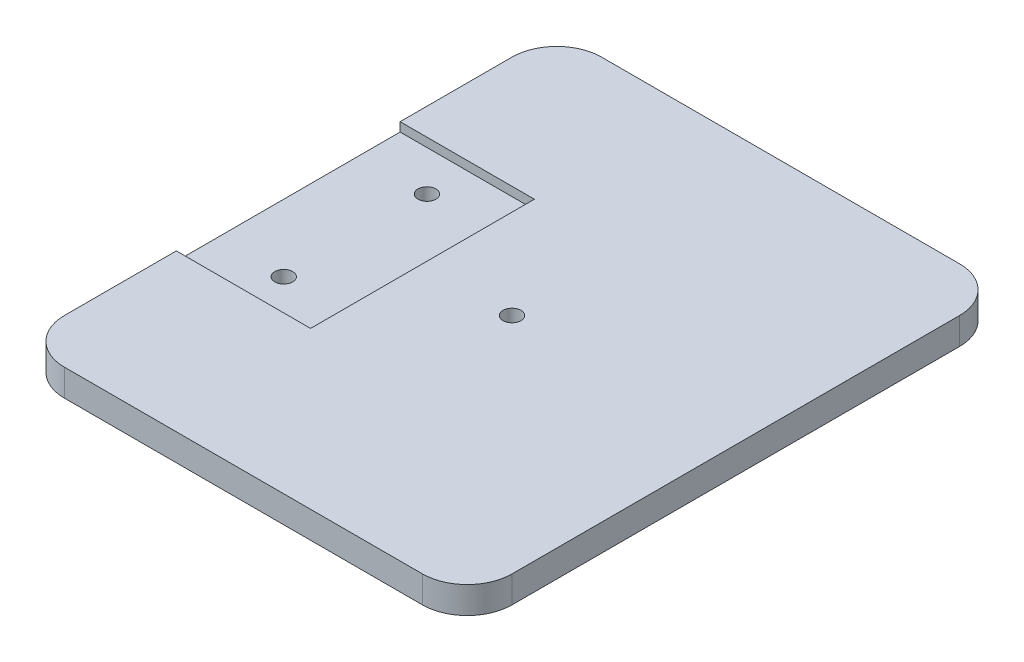
SolidWorks part; units mm, degrees
ref_plane "Front Plane" through (0, 0, 0) normal (0, 0, 1) x (1, 0, 0)
ref_plane "Top Plane" through (0, 0, 0) normal (0, 1, 0) x (1, 0, 0)
ref_plane "Right Plane" through (0, 0, 0) normal (1, 0, 0) x (0, 0, -1)
sketch "Sketch1" plane through (0, 0, 0) normal (0, 1, 0) x (1, 0, 0)
  line L1 (-31.0379, 28.304) -> (8.9621, 28.304)
  line L2 (-36.0379, 23.304) -> (-36.0379, -26.696)
  line L3 (-31.0379, -31.696) -> (8.9621, -31.696)
  line L4 (13.9621, 23.304) -> (13.9621, -26.696)
  arc A0 (8.9621, -31.696) -> (13.9621, -26.696) centre (8.9621, -26.696) ccw
  arc A1 (8.9621, 28.304) -> (13.9621, 23.304) centre (8.9621, 23.304) cw
  arc A2 (-31.0379, 28.304) -> (-36.0379, 23.304) centre (-31.0379, 23.304) ccw
  arc A3 (-36.0379, -26.696) -> (-31.0379, -31.696) centre (-31.0379, -26.696) ccw
  point P4 (0, 0)
  point P9 (13.9621, 28.304)
  point P12 (-36.0379, 28.304)
  point P15 (-36.0379, -31.696)
  dimension "D3" = 5
  dimension "D1" = 60
  dimension "D2" = 50
extrude "Boss-Extrude1" add sketch "Sketch1" along normal blind 3
sketch "Sketch2" plane through (0, 3, 0) normal (0, 1, 0) x (1, 0, 0)
  line L0 (-36.0379, 23.304) -> (-36.0379, -26.696) construction
  line L1 (-36.0379, 10.804) -> (-21.0379, 10.804)
  line L2 (-36.0379, 10.804) -> (-36.0379, -14.196)
  line L3 (-36.0379, -14.196) -> (-21.0379, -14.196)
  line L4 (-21.0379, 10.804) -> (-21.0379, -14.196)
  line L5 (8.9621, 28.304) -> (-31.0379, 28.304) construction
  dimension "D1" = 15
  dimension "D2" = 25
  dimension "D3" = 17.5
extrude "Cut-Extrude1" cut sketch "Sketch2" against normal blind 1
sketch "Sketch3" plane through (0, 2, 0) normal (0, 1, 0) x (1, 0, 0)
  line L0 (-21.0379, 10.804) -> (-36.0379, 10.804) construction
  line L1 (-36.0379, 10.804) -> (-36.0379, -14.196) construction
  line L2 (-36.0379, -14.196) -> (-21.0379, -14.196) construction
  circle A0 centre (-28.5379, 6.304) radius 1
  circle A1 centre (-28.5379, -9.696) radius 1
  dimension "D1" = 4.5
  dimension "D3" = 4.5
  dimension "D2" = 7.5
extrude "Cut-Extrude2" cut sketch "Sketch3" against normal blind 2
sketch "Sketch4" plane through (0, 3, 0) normal (0, 1, 0) x (1, 0, 0)
  line L0 (8.9621, 28.304) -> (-31.0379, 28.304) construction
  line L1 (13.9621, -26.696) -> (13.9621, 23.304) construction
  circle A0 centre (-11.0379, -1.696) radius 1
  dimension "D1" = 30
  dimension "D2" = 25
extrude "Cut-Extrude3" cut sketch "Sketch4" against normal blind 3
